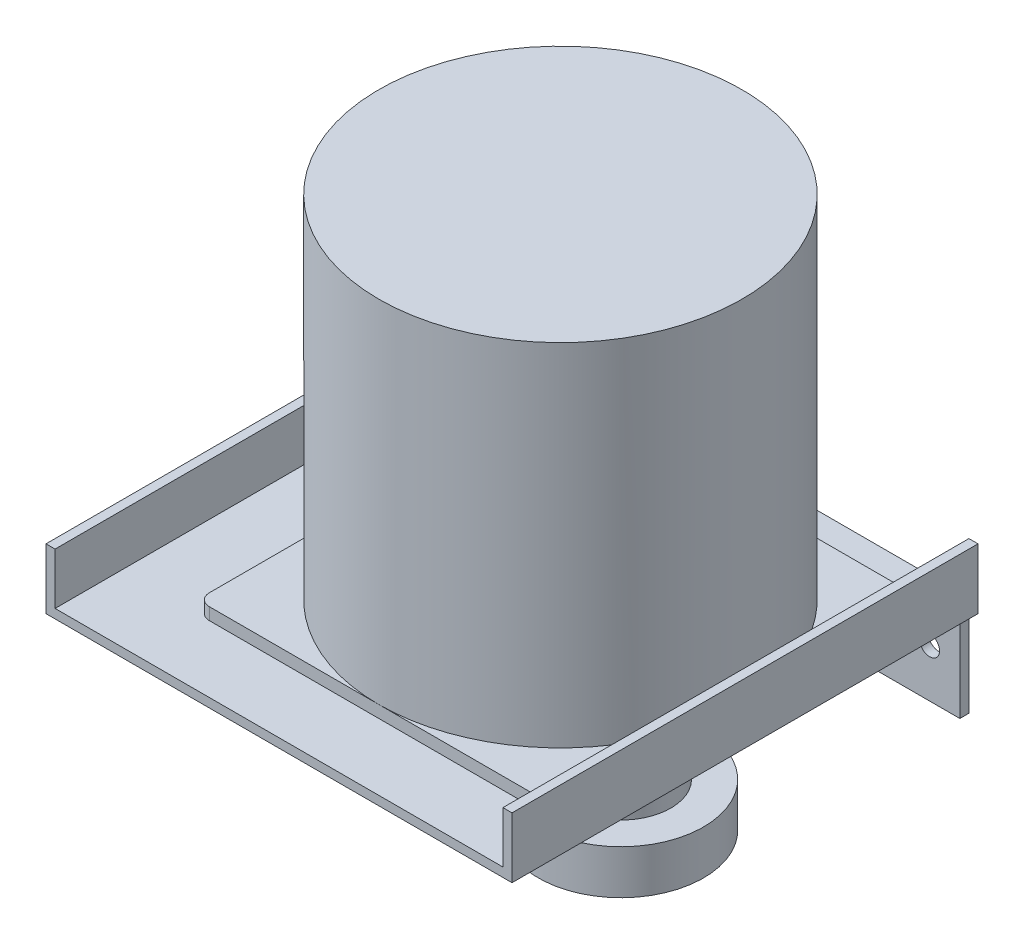
SolidWorks part; units mm, degrees
ref_plane "Спереди" through (0, 0, 0) normal (0, 0, 1) x (1, 0, 0)
ref_plane "Сверху" through (0, 0, 0) normal (0, 1, 0) x (1, 0, 0)
ref_plane "Справа" through (0, 0, 0) normal (1, 0, 0) x (0, 0, -1)
sketch "Эскиз1" plane through (0, 0, 0) normal (0, 1, 0) x (1, 0, 0)
  circle A0 centre (0, 0) radius 30
  dimension "D1" = 60
extrude "Бобышка-Вытянуть1" add sketch "Эскиз1" along normal blind 58
sketch "Эскиз2" plane through (0, 0, 0) normal (0, -1, 0) x (1, 0, 0)
  line L1 (-30, -30) -> (30, -30)
  line L2 (-30, -30) -> (-30, 30)
  line L3 (-30, 30) -> (30, 30)
  line L4 (30, -30) -> (30, 30)
  line L5 (-30, -30) -> (30, 30) construction
  line L6 (-30, 30) -> (30, -30) construction
  point P0 (0, 0)
extrude "Бобышка-Вытянуть2" add sketch "Эскиз2" along normal blind 2
fillet "Скругление1" radius 2 4 edges at (-30, -1, 30) (-30, -1, -30) (30, -1, -30) (30, -1, 30)
sketch "Эскиз3" plane through (0, -2, 0) normal (0, -1, 0) x (1, 0, 0)
  line L0 (-28, -30) -> (28, -30) construction
  line L1 (-44, -36) -> (33, -36)
  line L2 (-44, -36) -> (-44, 41)
  line L3 (-44, 41) -> (33, 41)
  line L4 (33, -36) -> (33, 41)
  line L5 (-44, -36) -> (33, 41) construction
  line L6 (-44, 41) -> (33, -36) construction
  line L7 (-30, 28) -> (-30, -28) construction
  point P0 (-5.5, 2.5)
  dimension "D1" = 77
  dimension "D2" = 77
  dimension "D3" = 6
  dimension "D4" = 14
extrude "Бобышка-Вытянуть3" add sketch "Эскиз3" along normal blind 1.5 contours L3 L4 L1 L2
sketch "Эскиз4" plane through (0, -2, 0) normal (0, 1, 0) x (1, 0, 0)
  line L0 (-44, 36) -> (33, 36) construction
  line L1 (33, -41) -> (31.5, -41)
  line L2 (33, -41) -> (33, 36)
  line L3 (33, 36) -> (31.5, 36)
  line L4 (31.5, -41) -> (31.5, 36)
  line L6 (-44, -41) -> (-42.5, -41)
  line L7 (-44, -41) -> (-44, 36)
  line L8 (-44, 36) -> (-42.5, 36)
  line L9 (-42.5, -41) -> (-42.5, 36)
  dimension "D1" = 1.5
  dimension "D2" = 1.5
extrude "Бобышка-Вытянуть4" add sketch "Эскиз4" along normal blind 8.5
sketch "Эскиз5" plane through (0, -3.5, 0) normal (0, -1, 0) x (1, 0, 0)
  line L1 (-42.5, -36) -> (31.5, -36)
  line L2 (-42.5, -36) -> (-42.5, -34.5)
  line L3 (-42.5, -34.5) -> (31.5, -34.5)
  line L4 (31.5, -36) -> (31.5, -34.5)
  line L5 (-44, -36) -> (33, -36) construction
  line L6 (-44, -36) -> (-44, 41) construction
  line L7 (33, -36) -> (33, 41) construction
  point P5 (25.9357, -33.3116)
  point P6 (0, 0)
  point P7 (-44, -34.5)
  point P8 (-40.7255, -34.4249)
  point P11 (-42.2244, -34.5)
  dimension "D1" = 1.5
  dimension "D2" = 1.5
  dimension "D3" = 1.5
  dimension "D4" = 74
extrude "Бобышка-Вытянуть5" add sketch "Эскиз5" along normal blind 15
sketch "Эскиз6" plane through (0, -3.5, 0) normal (0, -1, 0) x (1, 0, 0)
  line L0 (33, -36) -> (33, 41) construction
  line L1 (-42.5, -36) -> (31.5, -36) construction
  circle A0 centre (9.5, -0.5) radius 3.5
  point P0 (9.5, -0.5)
  dimension "D3" = 7
  dimension "D1" = 23.5
  dimension "D2" = 35.5
extrude "Бобышка-Вытянуть6" add sketch "Эскиз6" along normal blind 10
sketch "Эскиз7" plane through (0, -13.5, 0) normal (0, -1, 0) x (1, 0, 0)
  circle A0 centre (9.5, -0.5) radius 8.25
  dimension "D1" = 16.5
extrude "Бобышка-Вытянуть7" add sketch "Эскиз7" along normal blind 7.7 contours A0
sketch "Эскиз8" plane through (0, -21.2, 0) normal (0, -1, 0) x (1, 0, 0)
  circle A0 centre (9.5, -0.5) radius 13.65
  dimension "D1" = 27.3
extrude "Бобышка-Вытянуть8" add sketch "Эскиз8" along normal blind 7.3
sketch "Эскиз9" plane through (0, 0, -36) normal (0, 0, -1) x (-1, 0, 0)
  line L0 (-31.5, -18.5) -> (-31.5, -3.5) construction
  line L1 (42.5, -18.5) -> (42.5, -3.5) construction
  line L2 (42.5, -18.5) -> (-31.5, -18.5) construction
  point P0 (37.5, -10.5)
  point P1 (-26.5, -10.5)
  point P2 (0, 0)
  point P9 (29.5785, -18.5)
  dimension "D1" = 5
  dimension "D2" = 5
  dimension "D3" = 8
hole_wizard "Отверстие обработанное метчиком M41" positions "Эскиз10" profile "Эскиз11" tap size "M4" standard "DIN" end condition up to next
sketch "Эскиз10" plane through (0, 0, -36) normal (0, 0, -1) x (-1, 0, 0)
  point P0 (37.5, -10.5)
  point P3 (-26.5, -10.5)
sketch "Эскиз11" plane through (-37.5, -10.5, -36) normal (1, 0, 0) x (0, 1, 0)
  line L0 (0, 0) -> (0, 1.5)
  line L1 (0, 1.5) -> (1.65, 1.5)
  line L2 (1.65, 1.5) -> (1.65, 0)
  line L5 (1.65, 0) -> (0, 0)
  line L11 (0, -6.35) -> (0, 107.95) construction
  dimension "Диаметр проходного сверла" = 3.3
  dimension "Глубина проходного сверла" = 1.5
cosmetic thread "Отверстие резьбы1" parameters "D2"=4
cosmetic thread "Отверстие резьбы2" parameters "D2"=4
